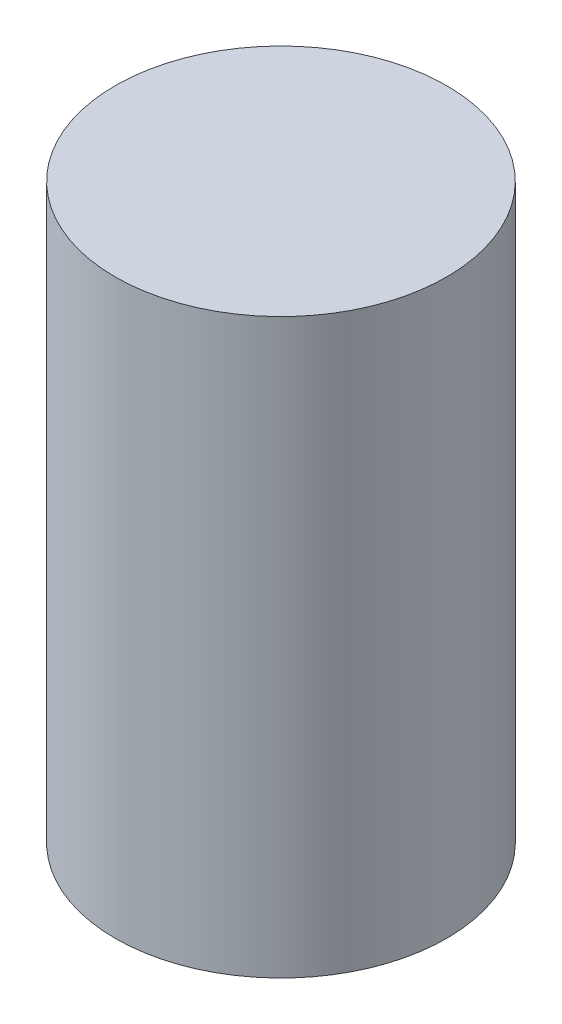
SolidWorks part; units mm, degrees
ref_plane "Front Plane" through (0, 0, 0) normal (0, 0, 1) x (1, 0, 0)
ref_plane "Top Plane" through (0, 0, 0) normal (0, 1, 0) x (1, 0, 0)
ref_plane "Right Plane" through (0, 0, 0) normal (1, 0, 0) x (0, 0, -1)
sketch "Sketch1" plane through (0, 0, 0) normal (0, 1, 0) x (1, 0, 0)
  circle A0 centre (0, 0) radius 20.25
  dimension "D1" = 40.5
extrude "Boss-Extrude1" add sketch "Sketch1" along normal blind 70
